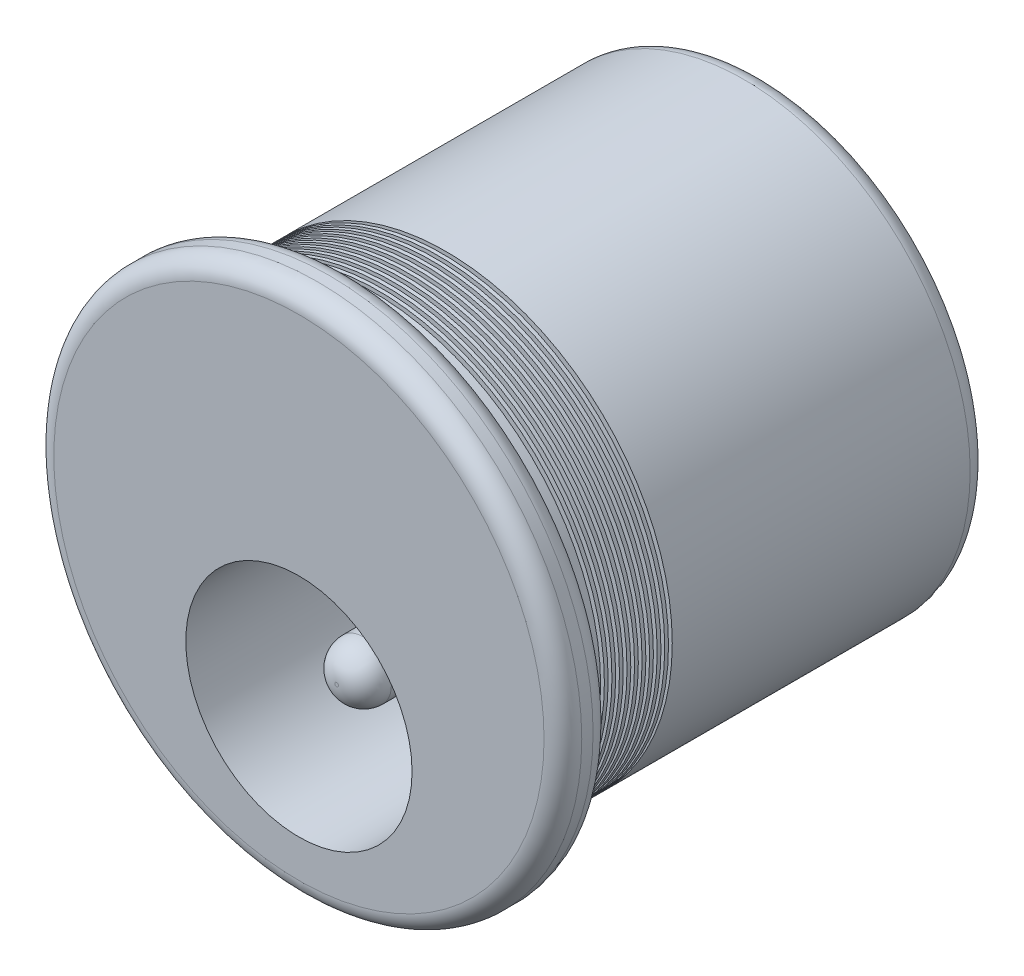
SolidWorks part; units mm, degrees
ref_plane "前视基准面" through (0, 0, 0) normal (0, 0, 1) x (1, 0, 0)
ref_plane "上视基准面" through (0, 0, 0) normal (0, 1, 0) x (1, 0, 0)
ref_plane "右视基准面" through (0, 0, 0) normal (1, 0, 0) x (0, 0, -1)
other "Configuration Table"
ref_plane "基准面1" through (0, 0, 0) normal (0, -1, 0) x (1, 0, 0)
sketch "草图1" plane through (0, 0, 0) normal (0, -1, 0) x (1, 0, 0)
  line L0 (7, 1.3) -> (0, 1.3)
  line L1 (0, 1.3) -> (0, -11)
  line L2 (0, -11) -> (6, -11)
  line L3 (6, -11) -> (6, -2.6)
  line L4 (6, -2.6) -> (5.75, -2.6)
  line L5 (5.75, -2.6) -> (5.75, -2.5)
  line L6 (5.75, -2.5) -> (6, -2.5)
  line L7 (6, -2.5) -> (6, -2.4)
  line L8 (6, -2.4) -> (5.75, -2.4)
  line L9 (5.75, -2.4) -> (5.75, -2.3)
  line L10 (5.75, -2.3) -> (6, -2.3)
  line L11 (6, -2.3) -> (6, -2.2)
  line L12 (6, -2.2) -> (5.75, -2.2)
  line L13 (5.75, -2.2) -> (5.75, -2.1)
  line L14 (5.75, -2.1) -> (6, -2.1)
  line L15 (6, -2.1) -> (6, -2)
  line L16 (6, -2) -> (5.75, -2)
  line L17 (5.75, -2) -> (5.75, -1.9)
  line L18 (5.75, -1.9) -> (6, -1.9)
  line L19 (6, -1.9) -> (6, -1.8)
  line L20 (6, -1.8) -> (5.75, -1.8)
  line L21 (5.75, -1.8) -> (5.75, -1.7)
  line L22 (5.75, -1.7) -> (6, -1.7)
  line L23 (6, -1.7) -> (6, -1.6)
  line L24 (6, -1.6) -> (5.75, -1.6)
  line L25 (5.75, -1.6) -> (5.75, -1.5)
  line L26 (5.75, -1.5) -> (6, -1.5)
  line L27 (6, -1.5) -> (6, -1.4)
  line L28 (6, -1.4) -> (5.75, -1.4)
  line L29 (5.75, -1.4) -> (5.75, -1.3)
  line L30 (5.75, -1.3) -> (6, -1.3)
  line L31 (6, -1.3) -> (6, -1.2)
  line L32 (6, -1.2) -> (5.75, -1.2)
  line L33 (5.75, -1.2) -> (5.75, -1.1)
  line L34 (5.75, -1.1) -> (6, -1.1)
  line L35 (6, -1.1) -> (6, -1)
  line L36 (6, -1) -> (5.75, -1)
  line L37 (5.75, -1) -> (5.75, -0.9)
  line L38 (5.75, -0.9) -> (6, -0.9)
  line L39 (6, -0.9) -> (6, -0.8)
  line L40 (6, -0.8) -> (5.75, -0.8)
  line L41 (5.75, -0.8) -> (5.75, -0.7)
  line L42 (5.75, -0.7) -> (6, -0.7)
  line L43 (6, -0.7) -> (6, 0)
  line L44 (6, 0) -> (7, 0)
  line L45 (7, 0) -> (7, 1.3)
  line L46 (0, 1.3) -> (0, -11) construction
  dimension "D1" = 5.75
  dimension "D2" = 6
  dimension "D3" = 7
  dimension "D4" = 8.4
  dimension "D5" = 8.5
  dimension "D6" = 8.6
  dimension "D7" = 8.7
  dimension "D8" = 8.8
  dimension "D9" = 8.9
  dimension "D10" = 9
  dimension "D11" = 9.1
  dimension "D12" = 9.2
  dimension "D13" = 9.3
  dimension "D14" = 9.4
  dimension "D15" = 9.5
  dimension "D16" = 9.6
  dimension "D17" = 9.7
  dimension "D18" = 9.8
  dimension "D19" = 9.9
  dimension "D20" = 10
  dimension "D21" = 10.1
  dimension "D22" = 10.2
  dimension "D23" = 10.3
  dimension "D24" = 11
  dimension "D25" = 12.3
revolve "旋转1" add sketch "草图1" angle 360 about L46
hole_wizard "Ø6.0 (6) 直径孔1" positions "草图3" profile "草图2" hole size "Ø6.0" standard "ANSI Metric"
sketch "草图3" plane through (0, 0, 1.3) normal (0, 0, 1) x (1, 0, 0)
  point P0 (0, -2.5)
sketch "草图2" plane through (0, -2.5, 1.3) normal (1, 0, 0) x (0, -1, 0)
  line L0 (0, 0) -> (0, 6)
  line L1 (0, 6) -> (3, 6)
  line L2 (3, 6) -> (3, 0)
  line L5 (3, 0) -> (0, 0)
  line L10 (0, 6) -> (-3, 6) construction
  line L11 (0, -6.35) -> (0, 107.95) construction
  dimension "孔直径" = 6
  dimension "孔深度" = 6
  dimension "导头角度" = 180
ref_plane "基准面2" through (0, -2.5, 0) normal (0, 1, 0) x (1, 0, 0)
sketch "草图4" plane through (0, -2.5, 0) normal (0, 1, 0) x (1, 0, 0)
  line L0 (0.75, 4.7) -> (0, 4.7)
  line L1 (0, 4.7) -> (0, -0.3)
  line L2 (0, -0.3) -> (0.75, -0.3)
  line L3 (0.75, -0.3) -> (0.75, 4.7)
  line L4 (0, 4.7) -> (0, -0.3) construction
  dimension "D1" = 0.75
  dimension "D2" = 5
revolve "旋转2" add sketch "草图4" angle 360 about L4
fillet "圆角1" radius 0.5 3 edges at (-6, 0, -11) (-7, 0, 0) (-7, 0, 1.3)
fillet "圆角2" radius 0.7 1 edges at (0.75, -2.5, 0.3)
